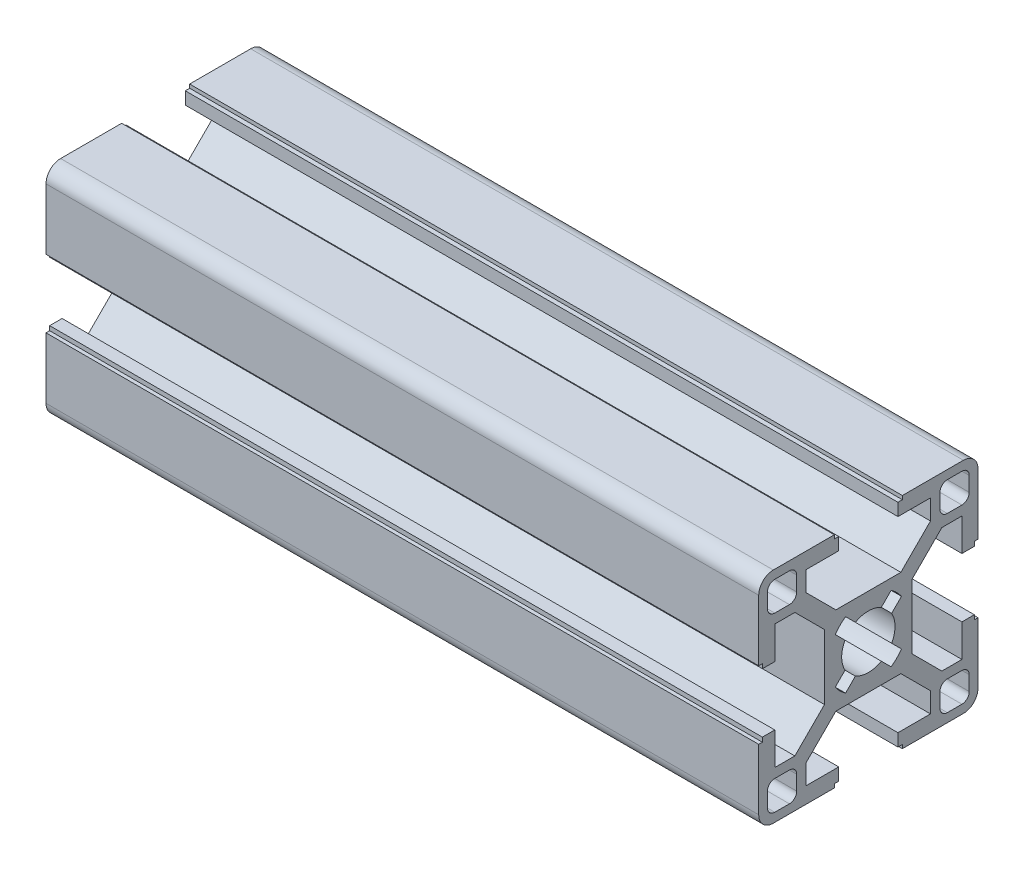
SolidWorks part; units mm, degrees
ref_plane "Ebene vorne" through (0, 0, 0) normal (0, 0, 1) x (1, 0, 0)
ref_plane "Ebene oben" through (0, 0, 0) normal (0, 1, 0) x (1, 0, 0)
ref_plane "Ebene rechts" through (0, 0, 0) normal (1, 0, 0) x (0, 0, -1)
sketch "Skizze1" plane through (0, 0, 0) normal (1, 0, 0) x (0, 0, -1)
  line L0 (8.5, 10.0556) -> (4.4444, 6)
  line L1 (13, 15) -> (-13, 15)
  line L2 (15, 13) -> (15, -13)
  line L3 (13, -15) -> (-13, -15)
  line L4 (-15, 13) -> (-15, -13)
  line L5 (15, 15) -> (-15, -15) construction
  line L6 (15, -15) -> (-15, 15) construction
  line L7 (6, 6) -> (-6, 6)
  line L8 (6, 6) -> (6, -6)
  line L9 (6, -6) -> (-6, -6)
  line L10 (-6, 6) -> (-6, -6)
  line L11 (6, 6) -> (-6, -6) construction
  line L12 (6, -6) -> (-6, 6) construction
  line L13 (8.5, 12.8) -> (-8.5, 12.8)
  line L14 (8.5, 12.8) -> (8.5, 6)
  line L15 (8.5, 6) -> (-8.5, 6)
  line L16 (-8.5, 12.8) -> (-8.5, 6)
  line L17 (4.05, 15) -> (-4.05, 15)
  line L18 (4.05, 15) -> (4.05, 12.8)
  line L19 (4.05, 12.8) -> (-4.05, 12.8)
  line L20 (-4.05, 15) -> (-4.05, 12.8)
  line L21 (-8.5, 10.0556) -> (-4.4444, 6)
  line L22 (3.1172, 4.5314) -> (1.7751, 3.1893)
  line L23 (-3.1172, 4.5314) -> (-1.7751, 3.1893)
  line L24 (15, -4.05) -> (12.8, -4.05)
  line L25 (4.05, 15) -> (4.6516, 15)
  line L26 (4.05, 15) -> (4.05, 14.5)
  line L27 (4.05, 14.5) -> (4.6516, 14.5)
  line L28 (4.6516, 15) -> (4.6516, 14.5)
  line L29 (-4.05, 15) -> (-4.6516, 15)
  line L30 (-4.05, 15) -> (-4.05, 14.5)
  line L31 (-4.05, 14.5) -> (-4.6516, 14.5)
  line L32 (-4.6516, 15) -> (-4.6516, 14.5)
  line L33 (15, -4.6516) -> (14.5, -4.6516)
  line L34 (14.5, -4.05) -> (14.5, -4.6516)
  line L35 (14.5, 4.05) -> (14.5, 4.6516)
  line L36 (15, 4.6516) -> (14.5, 4.6516)
  line L37 (15, 4.05) -> (12.8, 4.05)
  line L38 (12.8, 8.5) -> (6, 8.5)
  line L39 (12.8, -8.5) -> (12.8, 8.5)
  line L40 (12.8, -8.5) -> (6, -8.5)
  line L41 (10.0556, -8.5) -> (6, -4.4444)
  line L42 (10.0556, 8.5) -> (6, 4.4444)
  line L43 (4.5314, -3.1172) -> (3.1893, -1.7751)
  line L44 (4.5314, 3.1172) -> (3.1893, 1.7751)
  line L45 (-4.05, -15) -> (-4.05, -12.8)
  line L46 (-4.6516, -15) -> (-4.6516, -14.5)
  line L47 (-4.05, -14.5) -> (-4.6516, -14.5)
  line L48 (4.05, -14.5) -> (4.6516, -14.5)
  line L49 (4.6516, -15) -> (4.6516, -14.5)
  line L50 (4.05, -15) -> (4.05, -12.8)
  line L51 (8.5, -12.8) -> (8.5, -6)
  line L52 (-8.5, -12.8) -> (8.5, -12.8)
  line L53 (-8.5, -12.8) -> (-8.5, -6)
  line L54 (-8.5, -10.0556) -> (-4.4444, -6)
  line L55 (8.5, -10.0556) -> (4.4444, -6)
  line L56 (-3.1172, -4.5314) -> (-1.7751, -3.1893)
  line L57 (3.1172, -4.5314) -> (1.7751, -3.1893)
  line L58 (-15, 4.05) -> (-12.8, 4.05)
  line L59 (-15, 4.6516) -> (-14.5, 4.6516)
  line L60 (-14.5, 4.05) -> (-14.5, 4.6516)
  line L61 (-14.5, -4.05) -> (-14.5, -4.6516)
  line L62 (-15, -4.6516) -> (-14.5, -4.6516)
  line L63 (-15, -4.05) -> (-12.8, -4.05)
  line L64 (-12.8, -8.5) -> (-6, -8.5)
  line L65 (-12.8, 8.5) -> (-12.8, -8.5)
  line L66 (-12.8, 8.5) -> (-6, 8.5)
  line L67 (-10.0556, 8.5) -> (-6, 4.4444)
  line L68 (-10.0556, -8.5) -> (-6, -4.4444)
  line L69 (-4.5314, 3.1172) -> (-3.1893, 1.7751)
  line L70 (-4.5314, -3.1172) -> (-3.1893, -1.7751)
  line L71 (6, -8.5) -> (6, 8.5)
  line L72 (-8.5, -6) -> (8.5, -6)
  line L73 (-6, 8.5) -> (-6, -8.5)
  line L75 (12.8, 13.8) -> (10.8, 13.8)
  line L76 (13.8, 12.8) -> (13.8, 10.8)
  line L77 (12.8, 9.8) -> (10.8, 9.8)
  line L78 (9.8, 12.8) -> (9.8, 10.8)
  line L79 (13.8, 13.8) -> (9.8, 9.8) construction
  line L80 (13.8, 9.8) -> (9.8, 13.8) construction
  line L81 (-10.8, 13.8) -> (-12.8, 13.8)
  line L82 (-9.8, 12.8) -> (-9.8, 10.8)
  line L83 (-10.8, 9.8) -> (-12.8, 9.8)
  line L84 (-13.8, 12.8) -> (-13.8, 10.8)
  line L85 (-9.8, 13.8) -> (-13.8, 9.8) construction
  line L86 (-9.8, 9.8) -> (-13.8, 13.8) construction
  line L87 (12.8, -9.8) -> (10.8, -9.8)
  line L88 (13.8, -10.8) -> (13.8, -12.8)
  line L89 (12.8, -13.8) -> (10.8, -13.8)
  line L90 (9.8, -10.8) -> (9.8, -12.8)
  line L91 (13.8, -9.8) -> (9.8, -13.8) construction
  line L92 (13.8, -13.8) -> (9.8, -9.8) construction
  line L93 (-10.8, -9.8) -> (-12.8, -9.8)
  line L94 (-9.8, -10.8) -> (-9.8, -12.8)
  line L95 (-10.8, -13.8) -> (-12.8, -13.8)
  line L96 (-13.8, -10.8) -> (-13.8, -12.8)
  line L97 (-9.8, -9.8) -> (-13.8, -13.8) construction
  line L98 (-9.8, -13.8) -> (-13.8, -9.8) construction
  arc A0 (13, -15) -> (15, -13) centre (13, -13) ccw
  arc A1 (-13, -15) -> (-15, -13) centre (-13, -13) cw
  arc A2 (-15, 13) -> (-13, 15) centre (-13, 13) cw
  arc A3 (13, 15) -> (15, 13) centre (13, 13) cw
  circle A4 centre (0, 0) radius 3.65
  circle A5 centre (0, 0) radius 5.5
  circle A6 centre (0, 0) radius 3.65
  circle A7 centre (0, 0) radius 3.65
  circle A8 centre (0, 0) radius 3.65
  arc A9 (12.8, -13.8) -> (13.8, -12.8) centre (12.8, -12.8) ccw
  arc A10 (13.8, -10.8) -> (12.8, -9.8) centre (12.8, -10.8) ccw
  arc A11 (9.8, -12.8) -> (10.8, -13.8) centre (10.8, -12.8) ccw
  arc A12 (9.8, -10.8) -> (10.8, -9.8) centre (10.8, -10.8) cw
  arc A13 (-10.8, -13.8) -> (-9.8, -12.8) centre (-10.8, -12.8) ccw
  arc A14 (-10.8, -9.8) -> (-9.8, -10.8) centre (-10.8, -10.8) cw
  arc A15 (-13.8, -12.8) -> (-12.8, -13.8) centre (-12.8, -12.8) ccw
  arc A16 (-13.8, -10.8) -> (-12.8, -9.8) centre (-12.8, -10.8) cw
  arc A17 (-12.8, 9.8) -> (-13.8, 10.8) centre (-12.8, 10.8) cw
  arc A18 (-10.8, 9.8) -> (-9.8, 10.8) centre (-10.8, 10.8) ccw
  arc A19 (-13.8, 12.8) -> (-12.8, 13.8) centre (-12.8, 12.8) cw
  arc A20 (-10.8, 13.8) -> (-9.8, 12.8) centre (-10.8, 12.8) cw
  arc A21 (13.8, 10.8) -> (12.8, 9.8) centre (12.8, 10.8) cw
  arc A22 (10.8, 9.8) -> (9.8, 10.8) centre (10.8, 10.8) cw
  arc A23 (10.8, 13.8) -> (9.8, 12.8) centre (10.8, 12.8) ccw
  arc A24 (12.8, 13.8) -> (13.8, 12.8) centre (12.8, 12.8) cw
  point P0 (0, 0)
  point P33 (0, 12.8)
  point P34 (0, 15)
  point P36 (0, 12.8)
  point P50 (11.8, 11.8)
  point P122 (0, 0)
  point P125 (-11.8, 11.8)
  point P129 (0, 0)
  point P131 (11.8, -11.8)
  point P136 (-11.8, -11.8)
  dimension "D2" = 2
  dimension "D3" = 7.3
  dimension "D4" = 11
  dimension "D20" = 1
  dimension "D1" = 30
  dimension "D5" = 12
  dimension "D6" = 17
  dimension "D7" = 8.1
  dimension "D8" = 2.2
  dimension "D9" = 9
  dimension "D10" = 1.1
  dimension "D11" = 1.1
  dimension "D12" = 1
  dimension "D13" = 1
  dimension "D14" = 0.5
  dimension "D15" = 0.6016
  dimension "D18" = 4
  dimension "D19" = 1.2
  dimension "D16" = 4
  dimension "D17" = 4
extrude "Aufsatz-Linear austragen1" add sketch "Skizze1" along normal blind 130 contours A3 L1 L28 L27 L18 L13 L14 L38 L39 L37 L35 L36 L2 | L42 L38 L14 | L71 L15 L42 L14 L38 L0 | L42 L15 L8 | L7 L71 L0 | L38 L14 L0 | L7 L15 L10 L9 L8 A5 | L43 A5 L44 A4 | L22 A5 L23 A4 | L69 A5 L70 A4 | L56 A5 L57 A4 | L3 A0 L2 L33 L34 L24 L39 L40 L51 L52 L50 L48 L49 | L51 L40 L41 | L72 L71 L55 L40 L51 L41 | L8 L72 L41 | L55 L71 L9 | L55 L51 L40 | L73 L72 L68 L53 L64 L54 | L68 L72 L10 | L9 L73 L54 | L68 L64 L53 | L64 L53 L54 | A1 L3 L46 L47 L45 L52 L53 L64 L65 L63 L61 L62 L4 | A2 L4 L59 L60 L58 L65 L66 L16 L13 L20 L31 L32 L1 | L66 L67 L16 | L16 L66 L21 | L73 L21 L66 L16 L67 L15 | L21 L73 L15 | L15 L67 L10
scale "Scale1" scale about centroid uniform scaling no x scale factor 1 y scale factor 1.333333 z scale factor 1.333333
